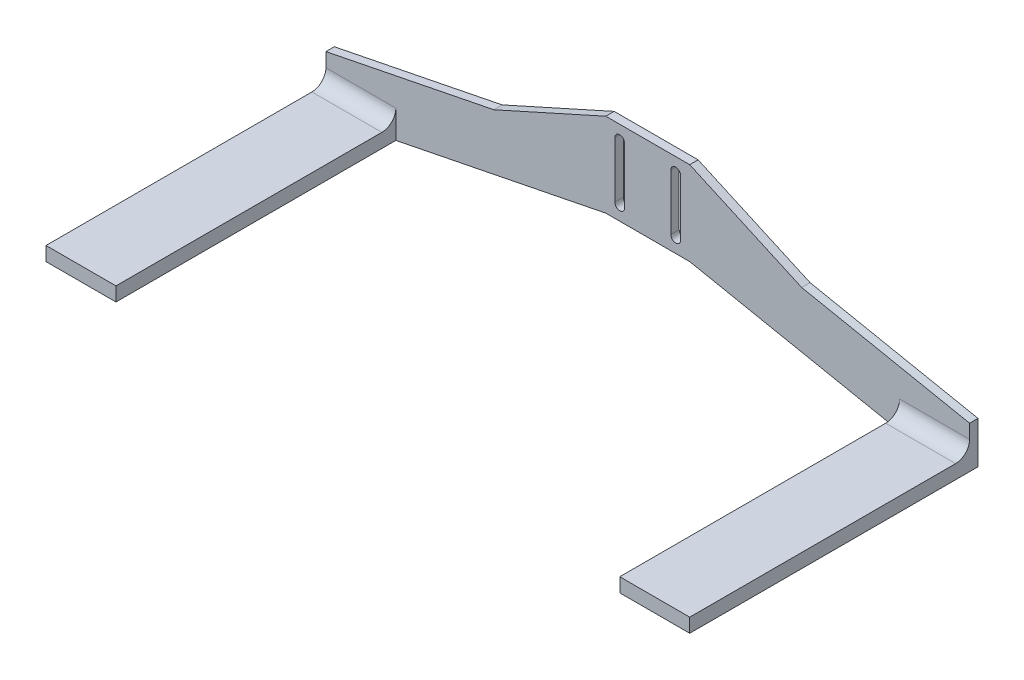
SolidWorks part; units mm, degrees
ref_plane "前视基准面" through (0, 0, 0) normal (0, 0, 1) x (1, 0, 0)
ref_plane "上视基准面" through (0, 0, 0) normal (0, 1, 0) x (1, 0, 0)
ref_plane "右视基准面" through (0, 0, 0) normal (1, 0, 0) x (0, 0, -1)
sketch "草图1" plane through (0, 0, 0) normal (0, 0, 1) x (1, 0, 0)
  line L0 (15, 0) -> (-15, 0) construction
  line L1 (-15, 15) -> (15, 15)
  line L2 (-15, 15) -> (-15, -15)
  line L3 (-15, -15) -> (15, -15)
  line L4 (15, 15) -> (15, -15)
  line L5 (-15, 15) -> (15, -15) construction
  line L6 (-15, -15) -> (15, 15) construction
  line L7 (-11.75, 10) -> (-8.25, 10)
  line L8 (-11.75, 10) -> (-11.75, -10)
  line L9 (-11.75, -10) -> (-8.25, -10)
  line L10 (-8.25, 10) -> (-8.25, -10)
  line L11 (-11.75, 10) -> (-8.25, -10) construction
  line L12 (-11.75, -10) -> (-8.25, 10) construction
  line L13 (11.75, 10) -> (8.25, 10)
  line L14 (11.75, 10) -> (11.75, -10)
  line L15 (11.75, -10) -> (8.25, -10)
  line L16 (8.25, 10) -> (8.25, -10)
  line L17 (11.75, 10) -> (8.25, -10) construction
  line L18 (11.75, -10) -> (8.25, 10) construction
  line L19 (-15, -15) -> (-90, -30)
  line L20 (-90, -30) -> (-115, -30)
  line L21 (-115, -30) -> (-115, -15)
  line L22 (-115, -15) -> (-55, -3)
  line L23 (-55, -3) -> (-15, 15)
  line L24 (0, 15) -> (0, -15) construction
  line L25 (55, -3) -> (15, 15)
  line L26 (115, -15) -> (55, -3)
  line L27 (115, -30) -> (115, -15)
  line L28 (90, -30) -> (115, -30)
  line L29 (15, -15) -> (90, -30)
  circle A0 centre (10, 10) radius 1.75
  circle A1 centre (10, -10) radius 1.75
  circle A2 centre (-10, -10) radius 1.75
  circle A3 centre (-10, 10) radius 1.75
  point P0 (0, 0)
  point P6 (-10, 0)
  point P11 (10, 0)
  point P19 (0, 0)
  point P34 (0, 0)
  dimension "D1" = 30
  dimension "D2" = 30
  dimension "D3" = 3.5
  dimension "D4" = 3.5
  dimension "D5" = 20
  dimension "D6" = 20
  dimension "D7" = 5
  dimension "D8" = 5
  dimension "D9" = 25
  dimension "D10" = 15
  dimension "D11" = 15
  dimension "D12" = 75
  dimension "D13" = 40
extrude "凸台-拉伸1" add sketch "草图1" along normal blind 3 contours L4 L1 L2 L3 A3 L10 A2 L8 A1 L16 A0 L14 | L23 L22 L21 L20 L19 L2 | L4 L29 L28 L27 L26 L25
sketch "草图2" plane through (0, 0, 0) normal (0, 0, -1) x (-1, 0, 0)
  line L0 (-115, -30) -> (-90, -30)
  line L1 (-90, -30) -> (-90, -25)
  line L2 (-90, -25) -> (-115, -25)
  line L3 (-115, -30) -> (-115, -15) construction
  line L4 (-115, -25) -> (-115, -30)
  line L5 (115, -30) -> (115, -25)
  line L6 (115, -30) -> (115, -15) construction
  line L7 (115, -30) -> (90, -30)
  line L8 (90, -30) -> (90, -25)
  line L9 (90, -25) -> (115, -25)
  dimension "D1" = 5
  dimension "D2" = 5
extrude "凸台-拉伸2" add sketch "草图2" against normal blind 100 from offset 3 offset against normal yes
fillet "圆角1" radius 5 2 edges at (102.5, -25, 3) (-102.5, -25, 3)
equation "\"t\"=5.07997"
